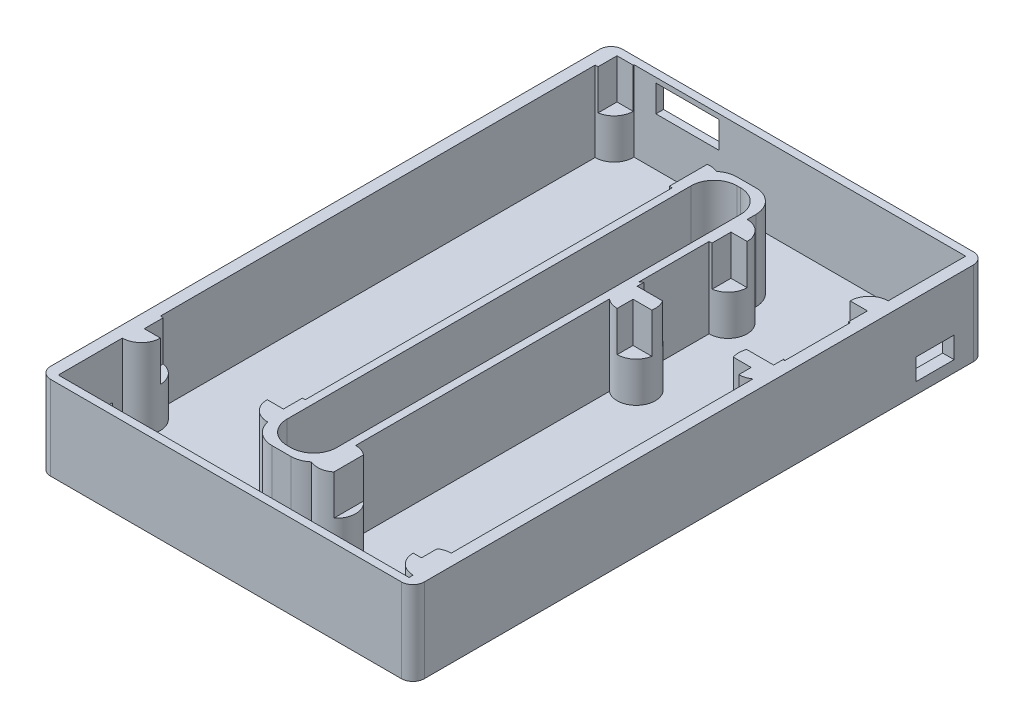
SolidWorks part; units mm, degrees
ref_plane "Front Plane" through (0, 0, 0) normal (0, 0, 1) x (1, 0, 0)
ref_plane "Top Plane" through (0, 0, 0) normal (0, 1, 0) x (1, 0, 0)
ref_plane "Right Plane" through (0, 0, 0) normal (1, 0, 0) x (0, 0, -1)
sketch "Sketch2" plane through (0, 0, 0) normal (0, 1, 0) x (1, 0, 0)
  line L1 (23, -37.5) -> (-23, -37.5)
  line L2 (24.5, -36) -> (24.5, 36)
  line L3 (23, 37.5) -> (-23, 37.5)
  line L4 (-24.5, -36) -> (-24.5, 36)
  line L5 (24.5, -37.5) -> (-24.5, 37.5) construction
  line L6 (24.5, 37.5) -> (-24.5, -37.5) construction
  line L15 (22.2754, -34.095) -> (-23.4369, 35.8728) construction
  line L16 (21.5, 35.8333) -> (-21.5, -35.8333) construction
  line L17 (23, -36.5) -> (-23, -36.5)
  line L18 (23, -36.5) -> (23, 36.5)
  line L19 (23, 36.5) -> (-23, 36.5)
  line L20 (-23, -36.5) -> (-23, 36.5)
  line L21 (23, -36.5) -> (-23, 36.5) construction
  line L22 (23, 36.5) -> (-23, -36.5) construction
  line L23 (0, 29.5) -> (0.5, 29.5)
  line L24 (-3, 26.5) -> (-3, -26.5)
  line L25 (0, -29.5) -> (0.5, -29.5)
  line L26 (3.5, 26.5) -> (3.5, -26.5)
  arc A0 (0.5, -29.5) -> (3.5, -26.5) centre (0.5, -26.5) ccw
  arc A1 (-3, -26.5) -> (0, -29.5) centre (0, -26.5) ccw
  arc A2 (0, 29.5) -> (-3, 26.5) centre (0, 26.5) ccw
  arc A3 (0.5, 29.5) -> (3.5, 26.5) centre (0.5, 26.5) cw
  arc A4 (-23, -37.5) -> (-24.5, -36) centre (-23, -36) cw
  arc A5 (23, -37.5) -> (24.5, -36) centre (23, -36) ccw
  arc A6 (24.5, 36) -> (23, 37.5) centre (23, 36) ccw
  arc A7 (-23, 37.5) -> (-24.5, 36) centre (-23, 36) ccw
  point P0 (0, 0)
  point P6 (0, 0)
  point P15 (-14.0764, 21.5455)
  point P18 (3.5, -29.5)
  point P20 (0, 0)
  point P26 (-3, -29.5)
  dimension "D3" = 46
  dimension "D7" = 3
  dimension "D5" = 1.5
  dimension "D1" = 75
  dimension "D2" = 49
  dimension "D4" = 73
  dimension "20" = 20
  dimension "D6" = 6.5
  dimension "D8" = 7
  dimension "D9" = 53
extrude "Boss-Extrude1" add sketch "Sketch2" against normal blind 11 contours L4 L1 L2 L3 L17 L20 L19 L18 | L20 L17 L18 L19 L23 A3 L26 A0 L25 A1 L24 A2
sketch "Sketch8" plane through (0, 0, 0) normal (0, 1, 0) x (1, 0, 0)
  line L1 (23, -36.5) -> (-23, -36.5)
  line L2 (23, -36.5) -> (23, 36.5)
  line L3 (23, 36.5) -> (-23, 36.5)
  line L4 (-23, -36.5) -> (-23, 36.5)
  line L5 (23, -36.5) -> (-23, 36.5) construction
  line L6 (23, 36.5) -> (-23, -36.5) construction
  line L8 (23, -36.5) -> (23, 36.5) construction
  line L9 (23, 36.5) -> (-23, 36.5) construction
  line L10 (-3, 26.5) -> (-3, -26.5) construction
  line L11 (0, 29.5) -> (0.5, 29.5)
  line L12 (-3, 26.5) -> (-3, -26.5)
  line L13 (0, -29.5) -> (0.5, -29.5)
  line L14 (3.5, 26.5) -> (3.5, -26.5)
  line L15 (3.5, 26.5) -> (3.5, -26.5) construction
  line L17 (-1, 30.5) -> (1.5, 30.5)
  line L18 (-4, 27.5) -> (-4, -27.5)
  line L19 (-1, -30.5) -> (1.5, -30.5)
  line L20 (4.5, 27.5) -> (4.5, -27.5)
  arc A0 (-3, -26.5) -> (0, -29.5) centre (0, -26.5) ccw
  arc A1 (0.5, -29.5) -> (3.5, -26.5) centre (0.5, -26.5) ccw
  arc A2 (0.5, 29.5) -> (3.5, 26.5) centre (0.5, 26.5) cw
  arc A3 (0, 29.5) -> (-3, 26.5) centre (0, 26.5) ccw
  arc A4 (-4, -27.5) -> (-1, -30.5) centre (-1, -27.5) ccw
  arc A5 (1.5, -30.5) -> (4.5, -27.5) centre (1.5, -27.5) ccw
  arc A6 (1.5, 30.5) -> (4.5, 27.5) centre (1.5, 27.5) cw
  arc A7 (-1, 30.5) -> (-4, 27.5) centre (-1, 27.5) ccw
  point P0 (0, 0)
  dimension "D3" = 3
  dimension "D9" = 3
  dimension "D1" = 7
  dimension "D2" = 19
  dimension "D4" = 6.5
  dimension "D5" = 1
  dimension "D6" = 1
  dimension "D7" = 1
  dimension "D8" = 1
extrude "Cut-Extrude1" cut sketch "Sketch8" against normal blind 10.5 contours L2 L1 L4 L3 | L12 A0 L13 A1 L14 A2 L11 A3 | L18 A4 L19 A5 L20 A6 L17 A7
sketch "Sketch9" plane through (0, -10.5, 0) normal (0, 1, 0) x (1, 0, 0)
  line L0 (21.58, 9.7933) -> (21.58, 11.5426) construction
  line L1 (-4.375, -25.6053) -> (-22.625, -25.6053) construction
  line L2 (-4.375, -25.6053) -> (-4.375, 36.3947) construction
  line L3 (-4.375, 36.3947) -> (-22.625, 36.3947) construction
  line L4 (-22.625, -25.6053) -> (-22.625, 36.3947) construction
  line L5 (-4.375, -25.6053) -> (-22.625, 36.3947) construction
  line L6 (-4.375, 36.3947) -> (-22.625, -25.6053) construction
  line L7 (4.875, 23.8426) -> (22.775, 23.8426) construction
  line L8 (4.875, 23.8426) -> (4.875, 11.5426) construction
  line L9 (4.875, 11.5426) -> (22.775, 11.5426) construction
  line L10 (22.775, 23.8426) -> (22.775, 11.5426) construction
  line L11 (4.875, 23.8426) -> (22.775, 11.5426) construction
  line L12 (4.875, 11.5426) -> (22.775, 23.8426) construction
  line L13 (6.08, 9.7933) -> (21.58, 9.7933) construction
  line L14 (6.08, 9.7933) -> (6.08, -33.4567) construction
  line L15 (6.08, -33.4567) -> (21.58, -33.4567) construction
  line L16 (21.58, 9.7933) -> (21.58, -33.4567) construction
  line L17 (6.08, 9.7933) -> (21.58, -33.4567) construction
  line L18 (6.08, -33.4567) -> (21.58, 9.7933) construction
  line L19 (6.08, 8.888) -> (6.08, 11.5426) construction
  line L20 (4.5, 27.5) -> (4.5, -27.5) construction
  line L21 (23, -36.5) -> (23, 36.5) construction
  line L22 (4.5, 27.5) -> (4.5, -27.5) construction
  line L23 (23, -36.5) -> (23, 36.5) construction
  line L24 (-4, 27.5) -> (-4, -27.5) construction
  line L25 (-23, -36.5) -> (-23, 36.5) construction
  line L42 (24.5, -36) -> (24.5, 36) construction
  line L43 (-24.5, -36) -> (-24.5, 36) construction
  line L44 (23, 37.5) -> (-23, 37.5) construction
  line L45 (24.5, -35.4567) -> (24.5, -31.4567)
  line L46 (4.5, 26.3426) -> (4.5, 21.3426)
  line L47 (-4, 27.5) -> (-4, 25)
  line L48 (-24.5, -27.6053) -> (-24.5, -23.6053)
  line L49 (-20.7576, 37.5) -> (-23, 37.5)
  line L50 (-24.5, 34.3947) -> (-24.5, 36)
  line L51 (24.5, 21.8426) -> (24.5, 25.8426)
  line L52 (4.5, 12.1527) -> (4.5, 8.2779)
  line L53 (-4, -23.1053) -> (-4, -27.5)
  line L54 (4.5, -25) -> (4.5, -27.5)
  line L55 (-23, 5.3947) -> (-22.625, 5.3947) construction
  line L56 (-4.375, 5.3947) -> (-4, 5.3947) construction
  line L57 (-4, 27.5) -> (-4, -27.5) construction
  arc A0 (4.5, 21.3426) -> (4.5, 26.3426) centre (4.5, 23.8426) ccw
  arc A1 (24.5, 25.8426) -> (24.5, 21.8426) centre (23, 23.8426) ccw
  circle A3 centre (21.58, 10.6679) radius 2.5
  circle A4 centre (6.08, 10.2153) radius 2.5
  arc A5 (24.5, -31.4567) -> (24.5, -35.4567) centre (23, -33.4567) ccw
  arc A6 (3.4583, -29.7726) -> (4.5, -25) centre (4.5, -27.5) ccw
  arc A7 (-4, -23.1053) -> (-3.9385, -28.1045) centre (-4, -25.6053) ccw
  arc A8 (-24.5, -27.6053) -> (-24.5, -23.6053) centre (-23, -25.6053) ccw
  arc A9 (-24.5, 34.3947) -> (-20.7576, 37.5) centre (-23, 36.3947) ccw
  arc A10 (-2.9583, 29.7726) -> (-4, 25) centre (-4, 27.5) ccw
  arc A27 (-4, -27.5) -> (-1, -30.5) centre (-1, -27.5) ccw construction
  arc A28 (1.5, -30.5) -> (4.5, -27.5) centre (1.5, -27.5) ccw construction
  arc A29 (4.5, 27.5) -> (1.5, 30.5) centre (1.5, 27.5) ccw construction
  arc A30 (-1, 30.5) -> (-4, 27.5) centre (-1, 27.5) ccw construction
  arc A31 (-23, 37.5) -> (-24.5, 36) centre (-23, 36) ccw construction
  arc A32 (-4, -27.5) -> (-3.9385, -28.1045) centre (-1, -27.5) ccw
  arc A33 (3.4583, -29.7726) -> (4.5, -27.5) centre (1.5, -27.5) ccw
  arc A34 (4.5, 27.5) -> (1.5, 30.5) centre (1.5, 27.5) ccw
  arc A35 (-2.9583, 29.7726) -> (-4, 27.5) centre (-1, 27.5) ccw
  arc A36 (-23, 37.5) -> (-24.5, 36) centre (-23, 36) ccw
  point P0 (-13.5, 5.3947)
  point P5 (13.825, 17.6926)
  point P10 (13.83, -11.8317)
  point P72 (21.42, -33.4567)
  point P73 (0, 0)
  point P81 (21.42, 11.3426)
  dimension "D8" = 1.58
  dimension "D10" = 5
  dimension "D1" = 62
  dimension "D2" = 18.25
  dimension "D3" = 17.9
  dimension "D4" = 43.25
  dimension "D5" = 15.5
  dimension "D6" = 12.3
  dimension "D7" = 0.375
extrude "Boss-Extrude2" add sketch "Sketch9" along normal up to surface (10.5 mm away) contours L47 A10 A35 | A36 L50 A9 L49 | L46 A0 | A1 L51 | A3 | A4 | L45 A5 | L53 A32 A7 | L48 A8 | A33 L54 A6 up to face at (0, 0, 0)
ref_plane "Plane1" through (0, -5.25, 0) normal (0, 1, 0) x (1, 0, 0)
sketch "Sketch10" plane through (0, -5.25, 0) normal (0, 1, 0) x (1, 0, 0)
  line L0 (6.08, -33.4567) -> (21.58, -33.4567) construction
  line L1 (21.58, 9.7933) -> (21.58, -33.4567) construction
  line L2 (6.08, 9.7933) -> (6.08, -33.4567) construction
  line L3 (6.08, 9.7933) -> (21.58, 9.7933) construction
  line L4 (22.775, 23.8426) -> (22.775, 11.5426) construction
  line L5 (4.875, 11.5426) -> (22.775, 11.5426) construction
  line L6 (4.875, 23.8426) -> (4.875, 11.5426) construction
  line L7 (4.875, 23.8426) -> (22.775, 23.8426) construction
  line L8 (-4.375, -25.6053) -> (-22.625, -25.6053) construction
  line L9 (-22.625, -25.6053) -> (-22.625, 36.3947) construction
  line L10 (-4.375, -25.6053) -> (-4.375, 36.3947) construction
  line L11 (-4.375, 36.3947) -> (-22.625, 36.3947) construction
  line L12 (6.08, -33.4567) -> (21.58, -33.4567)
  line L13 (21.58, 9.7933) -> (21.58, -33.4567)
  line L14 (6.08, 9.7933) -> (6.08, -33.4567)
  line L15 (6.08, 9.7933) -> (21.58, 9.7933)
  line L16 (22.775, 23.8426) -> (22.775, 11.5426)
  line L17 (4.875, 11.5426) -> (22.775, 11.5426)
  line L18 (4.875, 23.8426) -> (4.875, 11.5426)
  line L19 (4.875, 23.8426) -> (22.775, 23.8426)
  line L20 (-4.375, -25.6053) -> (-22.625, -25.6053)
  line L21 (-22.625, -25.6053) -> (-22.625, 36.3947)
  line L22 (-4.375, -25.6053) -> (-4.375, 36.3947)
  line L23 (-4.375, 36.3947) -> (-22.625, 36.3947)
  point P10 (0, 0)
  point P13 (0, 0)
extrude "Cut-Extrude3" cut sketch "Sketch10" along normal up to surface (5.25 mm away) up to face at (0, 0, 0)
sketch "Sketch11" plane through (23, 0, 0) normal (-1, 0, 0) x (0, 0, 1)
  line L0 (-26.3426, -10.5) -> (-36.5, -10.5) construction
  line L1 (-28.485, -9.5) -> (-33.485, -9.5)
  line L2 (-28.485, -9.5) -> (-28.485, -6.7)
  line L3 (-28.485, -6.7) -> (-33.485, -6.7)
  line L4 (-33.485, -9.5) -> (-33.485, -6.7)
  line L5 (-28.485, -9.5) -> (-33.485, -6.7) construction
  line L6 (-28.485, -6.7) -> (-33.485, -9.5) construction
  line L7 (-36.5, -10.5) -> (-36.5, 0) construction
  point P0 (-30.985, -8.1)
  dimension "D1" = 2.8
  dimension "D2" = 5
  dimension "D3" = 1
  dimension "D4" = 3.015
extrude "Cut-Extrude4" cut sketch "Sketch11" against normal blind 5
sketch "Sketch12" plane through (-23, 0, 0) normal (1, 0, 0) x (0, 0, -1)
  line L0 (-36.5, -10.5) -> (-28.1053, -10.5) construction
  line L1 (-29.39, -9.5) -> (-34.39, -9.5)
  line L2 (-29.39, -9.5) -> (-29.39, -6.7)
  line L3 (-29.39, -6.7) -> (-34.39, -6.7)
  line L4 (-34.39, -9.5) -> (-34.39, -6.7)
  line L5 (-29.39, -9.5) -> (-34.39, -6.7) construction
  line L6 (-29.39, -6.7) -> (-34.39, -9.5) construction
  line L7 (33.485, -6.7) -> (28.485, -6.7) construction
  line L8 (28.485, -6.7) -> (28.485, -9.5) construction
  line L9 (-36.5, -10.5) -> (-36.5, 0) construction
  point P0 (-31.89, -8.1)
  dimension "D1" = 1
  dimension "D4" = 2.11
extrude "Cut-Extrude5" cut sketch "Sketch12" against normal blind 5
sketch "Sketch14" plane through (0, 0, -36.5) normal (0, 0, 1) x (1, 0, 0)
  line L1 (-9.375, -4.15) -> (-17.625, -4.15)
  line L2 (-9.375, -4.15) -> (-9.375, -0.65)
  line L3 (-9.375, -0.65) -> (-17.625, -0.65)
  line L4 (-17.625, -4.15) -> (-17.625, -0.65)
  line L5 (-9.375, -4.15) -> (-17.625, -0.65) construction
  line L6 (-9.375, -0.65) -> (-17.625, -4.15) construction
  line L7 (26.95, -5.25) -> (-26.95, -5.25) construction
  point P0 (-13.5, -2.4)
  dimension "D1" = 4.6
  dimension "D2" = 9.125
  dimension "D3" = 8.25
  dimension "D4" = 3.5
extrude "Cut-Extrude6" cut sketch "Sketch14" against normal blind 5
